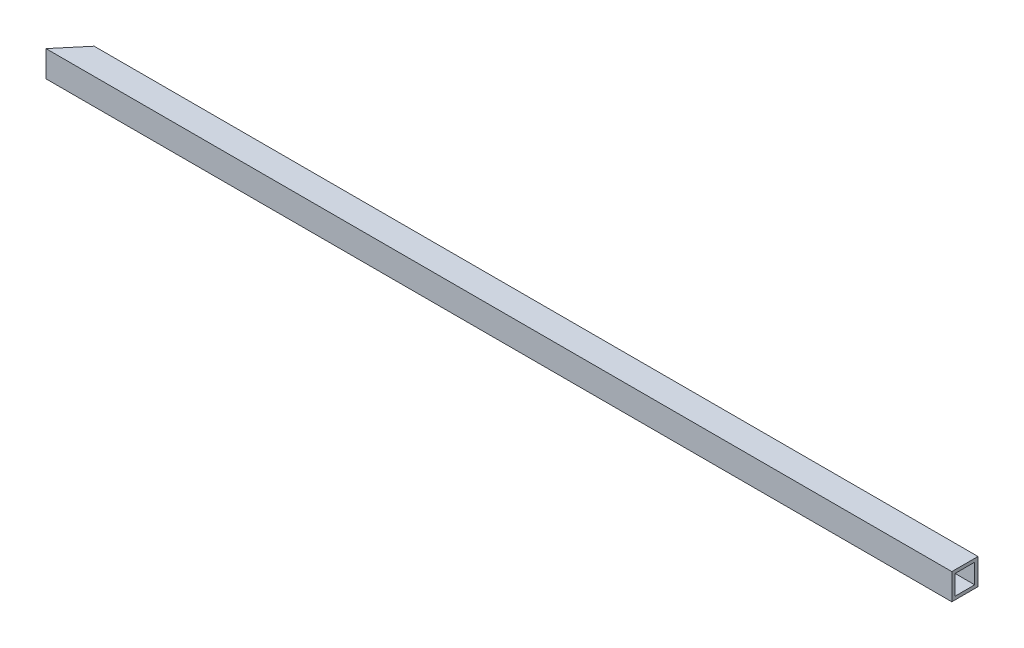
SolidWorks part; units mm, degrees
material "Plain Carbon Steel"
ref_plane "Front Plane" through (0, 0, 0) normal (0, 0, 1) x (1, 0, 0)
ref_plane "Top Plane" through (0, 0, 0) normal (0, 1, 0) x (1, 0, 0)
ref_plane "Right Plane" through (0, 0, 0) normal (1, 0, 0) x (0, 0, -1)
sketch "Sketch1" plane through (0, 0, 0) normal (1, 0, 0) x (0, 0, -1)
  line L0 (4.7625, 4.7625) -> (-4.7625, 4.7625)
  line L1 (6.35, 6.35) -> (-6.35, 6.35)
  line L2 (6.35, 6.35) -> (6.35, -6.35)
  line L3 (6.35, -6.35) -> (-6.35, -6.35)
  line L4 (-6.35, 6.35) -> (-6.35, -6.35)
  line L5 (6.35, 6.35) -> (-6.35, -6.35) construction
  line L6 (6.35, -6.35) -> (-6.35, 6.35) construction
  line L7 (-4.7625, 4.7625) -> (-4.7625, -4.7625)
  line L8 (4.7625, -4.7625) -> (-4.7625, -4.7625)
  line L9 (4.7625, 4.7625) -> (4.7625, -4.7625)
  dimension "D1" = 12.7
  dimension "D2" = 12.7
  dimension "D3" = 1.5875
extrude "Boss-Extrude1" add sketch "Sketch1" against normal blind 185.42 and the other way blind 254
sketch "Sketch2" plane through (0, 0, 0) normal (0, 1, 0) x (1, 0, 0)
  line L0 (-185.42, -6.35) -> (-135.9836, 52.566) construction
  line L1 (-185.42, -6.35) -> (-174.2505, 6.9613)
  line L2 (-185.42, -6.35) -> (-194.2478, 1.0574)
  line L3 (-174.2505, 6.9613) -> (-183.0782, 14.3687)
  line L4 (-194.2478, 1.0574) -> (-183.0782, 14.3687)
extrude "Cut-Extrude1" cut sketch "Sketch2" against normal through all and the other way through all
